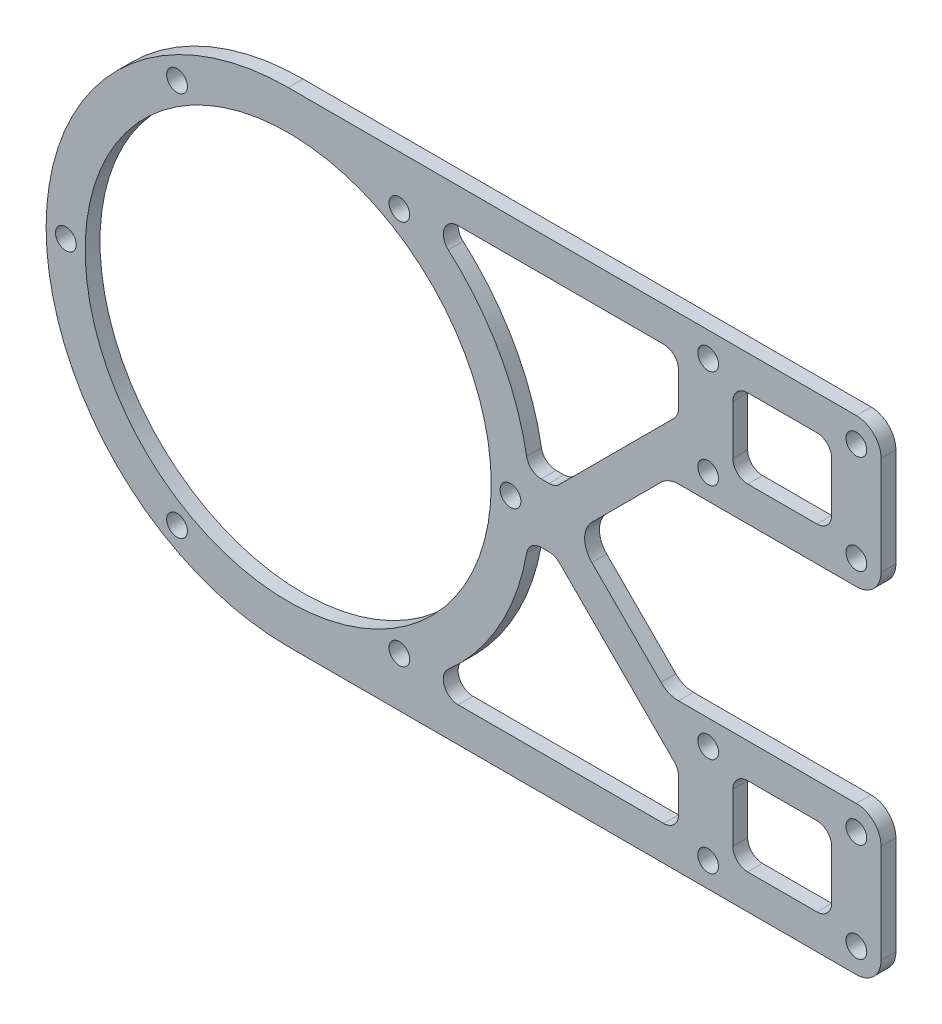
SolidWorks part; units mm, degrees
material "Thornel Mat VMA"
ref_plane "前视基准面" through (0, 0, 0) normal (0, 0, 1) x (1, 0, 0)
ref_plane "上视基准面" through (0, 0, 0) normal (0, 1, 0) x (1, 0, 0)
ref_plane "右视基准面" through (0, 0, 0) normal (1, 0, 0) x (0, 0, -1)
other "Configuration Table"
sketch "草图1" plane through (0, 0, 0) normal (0, 0, 1) x (1, 0, 0)
  line L0 (0, 49) -> (115, 49)
  line L1 (0, -49) -> (115, -49)
  line L2 (120, 44) -> (120, 24)
  line L3 (115, 19) -> (79, 19)
  line L4 (0, 0) -> (18.0163, 0) construction
  line L5 (115, -19) -> (79, -19)
  line L6 (120, -44) -> (120, -24)
  line L7 (75.4645, 17.5355) -> (61.4645, 3.5355)
  line L8 (75.4645, -17.5355) -> (61.4645, -3.5355)
  line L13 (93, -42) -> (107, -42)
  line L14 (90, -29) -> (90, -39)
  line L15 (107, -26) -> (93, -26)
  line L16 (110, -39) -> (110, -29)
  line L17 (93, -42) -> (107, -42)
  line L18 (90, -29) -> (90, -39)
  line L19 (107, -26) -> (93, -26)
  line L20 (110, -39) -> (110, -29)
  line L21 (34.3948, -42) -> (76, -42)
  line L22 (52.7868, -6) -> (51.2152, -6)
  line L23 (78.1213, -30.0919) -> (54.9081, -6.8787)
  line L24 (79, -39) -> (79, -32.2132)
  line L25 (34.3948, -42) -> (76, -42)
  line L26 (52.7868, -6) -> (51.2152, -6)
  line L27 (78.1213, -30.0919) -> (54.9081, -6.8787)
  line L28 (79, -39) -> (79, -32.2132)
  line L29 (93, 26) -> (107, 26)
  line L30 (90, 39) -> (90, 29)
  line L31 (107, 42) -> (93, 42)
  line L32 (110, 29) -> (110, 39)
  line L33 (93, 26) -> (107, 26)
  line L34 (90, 39) -> (90, 29)
  line L35 (107, 42) -> (93, 42)
  line L36 (110, 29) -> (110, 39)
  line L37 (51.2152, 6) -> (52.7868, 6)
  line L38 (76, 42) -> (34.3948, 42)
  line L39 (79, 32.2132) -> (79, 39)
  line L40 (54.9081, 6.8787) -> (78.1213, 30.0919)
  line L41 (51.2152, 6) -> (52.7868, 6)
  line L42 (76, 42) -> (34.3948, 42)
  line L43 (79, 32.2132) -> (79, 39)
  line L44 (54.9081, 6.8787) -> (78.1213, 30.0919)
  circle A0 centre (0, 0) radius 45 construction
  circle A1 centre (-45, 0) radius 2.1
  circle A2 centre (-22.5, 38.9711) radius 2.1
  circle A3 centre (22.5, 38.9711) radius 2.1
  circle A4 centre (45, 0) radius 2.1
  circle A5 centre (22.5, -38.9711) radius 2.1
  circle A6 centre (-22.5, -38.9711) radius 2.1
  circle A7 centre (0, 0) radius 41.1
  arc A8 (0, 49) -> (0, -49) centre (0, 0) ccw
  arc A9 (79, -19) -> (75.4645, -17.5355) centre (79, -14) cw
  arc A10 (79, 19) -> (75.4645, 17.5355) centre (79, 14) ccw
  arc A11 (61.4645, 3.5355) -> (61.4645, -3.5355) centre (65, 0) ccw
  arc A12 (115, -49) -> (120, -44) centre (115, -44) ccw
  arc A13 (115, -19) -> (120, -24) centre (115, -24) cw
  arc A14 (120, 24) -> (115, 19) centre (115, 24) cw
  arc A15 (115, 49) -> (120, 44) centre (115, 44) cw
  arc A20 (90, -39) -> (93, -42) centre (93, -39) ccw
  arc A21 (93, -26) -> (90, -29) centre (93, -29) ccw
  arc A22 (110, -29) -> (107, -26) centre (107, -29) ccw
  arc A23 (107, -42) -> (110, -39) centre (107, -39) ccw
  arc A24 (90, -39) -> (93, -42) centre (93, -39) ccw
  arc A25 (93, -26) -> (90, -29) centre (93, -29) ccw
  arc A26 (110, -29) -> (107, -26) centre (107, -29) ccw
  arc A27 (107, -42) -> (110, -39) centre (107, -39) ccw
  arc A28 (90, 29) -> (93, 26) centre (93, 29) ccw
  arc A29 (93, 42) -> (90, 39) centre (93, 39) ccw
  arc A30 (32.4105, -36.75) -> (34.3948, -42) centre (34.3948, -39) ccw
  arc A31 (32.4105, -36.75) -> (48.2605, -8.4808) centre (0, 0) ccw
  arc A32 (51.2152, -6) -> (48.2605, -8.4808) centre (51.2152, -9) ccw
  arc A33 (54.9081, -6.8787) -> (52.7868, -6) centre (52.7868, -9) ccw
  arc A34 (79, -32.2132) -> (78.1213, -30.0919) centre (76, -32.2132) ccw
  arc A35 (76, -42) -> (79, -39) centre (76, -39) ccw
  arc A36 (32.4105, -36.75) -> (34.3948, -42) centre (34.3948, -39) ccw
  arc A37 (32.4105, -36.75) -> (48.2605, -8.4808) centre (0, 0) ccw
  arc A38 (51.2152, -6) -> (48.2605, -8.4808) centre (51.2152, -9) ccw
  arc A39 (54.9081, -6.8787) -> (52.7868, -6) centre (52.7868, -9) ccw
  arc A40 (79, -32.2132) -> (78.1213, -30.0919) centre (76, -32.2132) ccw
  arc A41 (76, -42) -> (79, -39) centre (76, -39) ccw
  arc A42 (110, 39) -> (107, 42) centre (107, 39) ccw
  arc A43 (107, 26) -> (110, 29) centre (107, 29) ccw
  arc A44 (90, 29) -> (93, 26) centre (93, 29) ccw
  arc A45 (93, 42) -> (90, 39) centre (93, 39) ccw
  arc A46 (110, 39) -> (107, 42) centre (107, 39) ccw
  arc A47 (107, 26) -> (110, 29) centre (107, 29) ccw
  arc A50 (48.2605, 8.4808) -> (51.2152, 6) centre (51.2152, 9) ccw
  arc A51 (48.2605, 8.4808) -> (32.4105, 36.75) centre (0, 0) ccw
  arc A52 (34.3948, 42) -> (32.4105, 36.75) centre (34.3948, 39) ccw
  arc A53 (79, 39) -> (76, 42) centre (76, 39) ccw
  arc A54 (78.1213, 30.0919) -> (79, 32.2132) centre (76, 32.2132) ccw
  arc A55 (52.7868, 6) -> (54.9081, 6.8787) centre (52.7868, 9) ccw
  arc A56 (48.2605, 8.4808) -> (51.2152, 6) centre (51.2152, 9) ccw
  arc A57 (48.2605, 8.4808) -> (32.4105, 36.75) centre (0, 0) ccw
  arc A58 (34.3948, 42) -> (32.4105, 36.75) centre (34.3948, 39) ccw
  arc A59 (79, 39) -> (76, 42) centre (76, 39) ccw
  arc A60 (78.1213, 30.0919) -> (79, 32.2132) centre (76, 32.2132) ccw
  arc A61 (52.7868, 6) -> (54.9081, 6.8787) centre (52.7868, 9) ccw
  point P18 (0, 0)
  point P30 (76.9289, -19)
  point P33 (76.9289, 19)
  point P36 (57.9289, 0)
  point P39 (120, -49)
  point P42 (120, -19)
  point P45 (120, 19)
  point P48 (120, 49)
  dimension "D1" = 90
  dimension "D2" = 4.2
  dimension "D4" = 82.2
  dimension "D5" = 49
  dimension "D8" = 5
  dimension "D9" = 5
  dimension "D6" = 30
  dimension "D7" = 45
  dimension "D10" = 20
  dimension "D11" = 120
  dimension "D12" = 0
  dimension "D13" = 0
  dimension "D14" = 0
  dimension "D15" = 0
  dimension "D3" = 6
extrude "凸台-拉伸1" add sketch "草图1" along normal blind 3
sketch "草图2" plane through (0, 0, 0) normal (0, 0, 1) x (1, 0, 0)
  line L0 (120, 34) -> (97.6002, 34) construction
  line L2 (0, 0) -> (15.5153, 0) construction
  line L3 (120, 24) -> (120, 44) construction
  line L4 (85, -44) -> (115, -24) construction
  line L5 (85, 24) -> (115, 24) construction
  line L6 (85, 24) -> (85, 44) construction
  line L7 (85, 44) -> (115, 44) construction
  line L8 (115, 24) -> (115, 44) construction
  line L9 (85, 24) -> (115, 44) construction
  line L10 (85, 44) -> (115, 24) construction
  line L11 (85, -24) -> (115, -44) construction
  line L12 (115, -24) -> (115, -44) construction
  line L13 (85, -44) -> (115, -44) construction
  line L14 (85, -24) -> (85, -44) construction
  line L15 (85, -24) -> (115, -24) construction
  circle A0 centre (85, 44) radius 2.1
  circle A1 centre (115, 44) radius 2.1
  circle A3 centre (115, 24) radius 2.1
  circle A4 centre (85, 24) radius 2.1
  circle A5 centre (85, -24) radius 2.1
  circle A6 centre (115, -24) radius 2.1
  circle A7 centre (115, -44) radius 2.1
  circle A8 centre (85, -44) radius 2.1
  point P3 (120, 34)
  point P8 (100, 34)
  point P27 (100, -34)
  dimension "D1" = 4.2
  dimension "D2" = 4.2
  dimension "D3" = 30
  dimension "D4" = 20
  dimension "D5" = 5
extrude "切除-拉伸1" cut sketch "草图2" along normal blind 3
